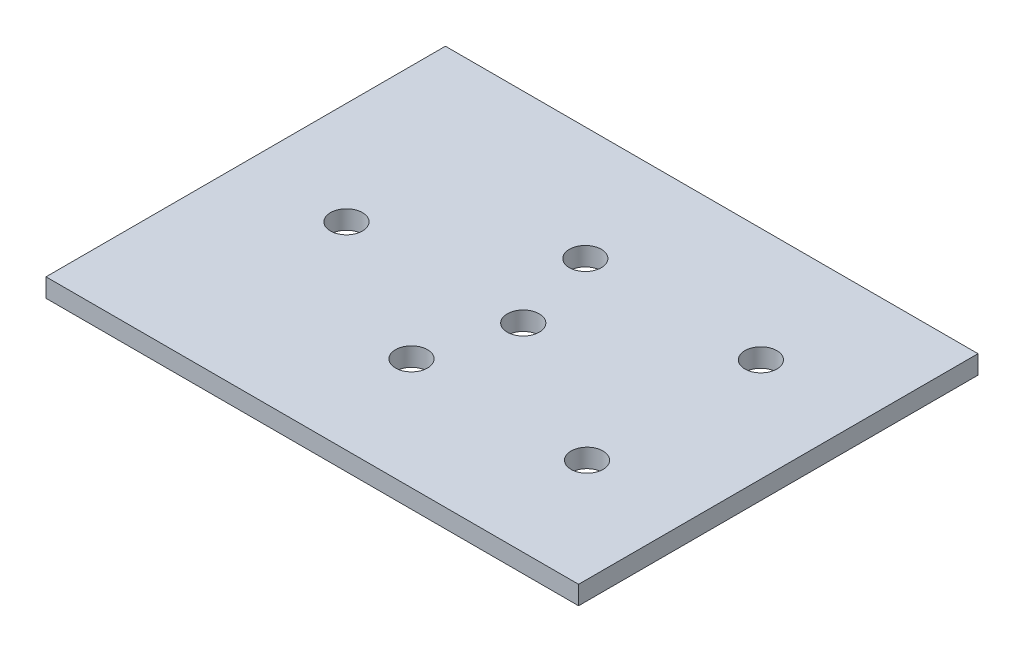
SolidWorks part; units mm, degrees
ref_plane "Front Plane" through (0, 0, 0) normal (0, 0, 1) x (1, 0, 0)
ref_plane "Top Plane" through (0, 0, 0) normal (0, 1, 0) x (1, 0, 0)
ref_plane "Right Plane" through (0, 0, 0) normal (1, 0, 0) x (0, 0, -1)
sketch "Sketch1" plane through (0, 0, 0) normal (0, 1, 0) x (1, 0, 0)
  line L0 (-63.449, 23.2484) -> (36.551, 23.2484)
  line L1 (36.551, 23.2484) -> (36.551, -51.7516)
  line L2 (-63.449, 23.2484) -> (-63.449, -51.7516)
  line L3 (-63.449, -51.7516) -> (36.551, -51.7516)
extrude "Boss-Extrude1" add sketch "Sketch1" along normal blind 3.5
hole_wizard "Ø6.0mm Dowel Hole1" positions "Sketch2" profile "Sketch3" hole size "Ø6.0" standard "ANSI Metric"
sketch "Sketch2" plane through (-137.5284, 0, 99.0346) normal (0, -1, 0) x (-1, 0, 0)
  point P0 (-156.2989, 100.9147)
sketch "Sketch3" plane through (18.7704, 0, -1.8801) normal (1, 0, 0) x (0, 0, -1)
  line L0 (0, 0) -> (0, 7.0026)
  line L1 (0, 7.0026) -> (3, 5.2)
  line L2 (3, 5.2) -> (3, 0)
  line L3 (3, 0) -> (0, 0)
  line L4 (0, 7.0026) -> (-3, 5.2) construction
  line L5 (0, -6.35) -> (0, 107.95) construction
  dimension "Hole Dia." = 6
  dimension "Hole Depth" = 5.2
  dimension "Drill Angle" = 118
hole_wizard "Ø6.0mm Dowel Hole2" positions "Sketch4" profile "Sketch5" hole size "Ø6.0" standard "ANSI Metric"
sketch "Sketch4" plane through (-137.5284, 0, 99.0346) normal (0, -1, 0) x (-1, 0, 0)
  point P0 (-123.3367, 100.9147)
sketch "Sketch5" plane through (-14.1917, 0, -1.8801) normal (1, 0, 0) x (0, 0, -1)
  line L0 (0, 0) -> (0, 7.0026)
  line L1 (0, 7.0026) -> (3, 5.2)
  line L2 (3, 5.2) -> (3, 0)
  line L3 (3, 0) -> (0, 0)
  line L4 (0, 7.0026) -> (-3, 5.2) construction
  line L5 (0, -6.35) -> (0, 107.95) construction
  dimension "Hole Dia." = 6
  dimension "Hole Depth" = 5.2
  dimension "Drill Angle" = 118
hole_wizard "Ø6.0mm Dowel Hole3" positions "Sketch6" profile "Sketch7" hole size "Ø6.0" standard "ANSI Metric"
sketch "Sketch6" plane through (-137.5284, 0, 99.0346) normal (0, -1, 0) x (-1, 0, 0)
  point P0 (-156.2989, 68.1913)
sketch "Sketch7" plane through (18.7704, 0, 30.8433) normal (1, 0, 0) x (0, 0, -1)
  line L0 (0, 0) -> (0, 7.0026)
  line L1 (0, 7.0026) -> (3, 5.2)
  line L2 (3, 5.2) -> (3, 0)
  line L3 (3, 0) -> (0, 0)
  line L4 (0, 7.0026) -> (-3, 5.2) construction
  line L5 (0, -6.35) -> (0, 107.95) construction
  dimension "Hole Dia." = 6
  dimension "Hole Depth" = 5.2
  dimension "Drill Angle" = 118
hole_wizard "Ø6.0mm Dowel Hole4" positions "Sketch8" profile "Sketch9" hole size "Ø6.0" standard "ANSI Metric"
sketch "Sketch8" plane through (-137.5284, 0, 99.0346) normal (0, -1, 0) x (-1, 0, 0)
  point P0 (-123.3367, 68.1913)
sketch "Sketch9" plane through (-14.1917, 0, 30.8433) normal (1, 0, 0) x (0, 0, -1)
  line L0 (0, 0) -> (0, 7.0026)
  line L1 (0, 7.0026) -> (3, 5.2)
  line L2 (3, 5.2) -> (3, 0)
  line L3 (3, 0) -> (0, 0)
  line L4 (0, 7.0026) -> (-3, 5.2) construction
  line L5 (0, -6.35) -> (0, 107.95) construction
  dimension "Hole Dia." = 6
  dimension "Hole Depth" = 5.2
  dimension "Drill Angle" = 118
hole_wizard "Ø6.0mm Dowel Hole5" positions "Sketch10" profile "Sketch11" hole size "Ø6.0" standard "ANSI Metric"
sketch "Sketch10" plane through (-137.5284, 0, 99.0346) normal (0, -1, 0) x (-1, 0, 0)
  point P0 (-154.6989, 100.9005)
sketch "Sketch11" plane through (17.1704, 0, -1.8659) normal (1, 0, 0) x (0, 0, -1)
  line L0 (0, 0) -> (0, 7.0026)
  line L1 (0, 7.0026) -> (3, 5.2)
  line L2 (3, 5.2) -> (3, 0)
  line L3 (3, 0) -> (0, 0)
  line L4 (0, 7.0026) -> (-3, 5.2) construction
  line L5 (0, -6.35) -> (0, 107.95) construction
  dimension "Hole Dia." = 6
  dimension "Hole Depth" = 5.2
  dimension "Drill Angle" = 118
hole_wizard "Ø6.0mm Dowel Hole6" positions "Sketch12" profile "Sketch13" hole size "Ø6.0" standard "ANSI Metric"
sketch "Sketch12" plane through (-137.5284, 0, 99.0346) normal (0, -1, 0) x (-1, 0, 0)
  point P0 (-121.7367, 100.9005)
sketch "Sketch13" plane through (-15.7917, 0, -1.8659) normal (1, 0, 0) x (0, 0, -1)
  line L0 (0, 0) -> (0, 7.0026)
  line L1 (0, 7.0026) -> (3, 5.2)
  line L2 (3, 5.2) -> (3, 0)
  line L3 (3, 0) -> (0, 0)
  line L4 (0, 7.0026) -> (-3, 5.2) construction
  line L5 (0, -6.35) -> (0, 107.95) construction
  dimension "Hole Dia." = 6
  dimension "Hole Depth" = 5.2
  dimension "Drill Angle" = 118
hole_wizard "Ø6.0mm Dowel Hole7" positions "Sketch14" profile "Sketch15" hole size "Ø6.0" standard "ANSI Metric"
sketch "Sketch14" plane through (-137.5284, 0, 99.0346) normal (0, -1, 0) x (-1, 0, 0)
  point P0 (-154.6989, 68.2553)
sketch "Sketch15" plane through (17.1704, 0, 30.7793) normal (1, 0, 0) x (0, 0, -1)
  line L0 (0, 0) -> (0, 7.0026)
  line L1 (0, 7.0026) -> (3, 5.2)
  line L2 (3, 5.2) -> (3, 0)
  line L3 (3, 0) -> (0, 0)
  line L4 (0, 7.0026) -> (-3, 5.2) construction
  line L5 (0, -6.35) -> (0, 107.95) construction
  dimension "Hole Dia." = 6
  dimension "Hole Depth" = 5.2
  dimension "Drill Angle" = 118
hole_wizard "Ø6.0mm Dowel Hole8" positions "Sketch16" profile "Sketch17" hole size "Ø6.0" standard "ANSI Metric"
sketch "Sketch16" plane through (-137.5284, 0, 99.0346) normal (0, -1, 0) x (-1, 0, 0)
  point P0 (-121.7367, 68.2553)
sketch "Sketch17" plane through (-15.7917, 0, 30.7793) normal (1, 0, 0) x (0, 0, -1)
  line L0 (0, 0) -> (0, 7.0026)
  line L1 (0, 7.0026) -> (3, 5.2)
  line L2 (3, 5.2) -> (3, 0)
  line L3 (3, 0) -> (0, 0)
  line L4 (0, 7.0026) -> (-3, 5.2) construction
  line L5 (0, -6.35) -> (0, 107.95) construction
  dimension "Hole Dia." = 6
  dimension "Hole Depth" = 5.2
  dimension "Drill Angle" = 118
hole_wizard "Ø6.0mm Dowel Hole9" positions "Sketch18" profile "Sketch19" hole size "Ø6.0" standard "ANSI Metric" end condition through all
sketch "Sketch18" plane through (-137.5284, 0, 99.0346) normal (0, -1, 0) x (-1, 0, 0)
  point P0 (-93.3466, 84.4369)
sketch "Sketch19" plane through (-44.1818, 0, 14.5977) normal (1, 0, 0) x (0, 0, -1)
  line L0 (0, 0) -> (0, 3.5)
  line L1 (0, 3.5) -> (3, 3.5)
  line L2 (3, 3.5) -> (3, 0)
  line L3 (3, 0) -> (0, 0)
  line L4 (0, -6.35) -> (0, 107.95) construction
  dimension "Thru Hole Dia." = 6
  dimension "Thru Hole Depth" = 3.5
hole_wizard "Ø6.0mm Dowel Hole10" positions "Sketch20" profile "Sketch21" hole size "Ø6.0" standard "AS" end condition through all
sketch "Sketch20" plane through (-137.5284, 0, 99.0346) normal (0, -1, 0) x (-1, 0, 0)
  point P0 (-126.3997, 84.5766)
sketch "Sketch21" plane through (-11.1287, 0, 14.458) normal (1, 0, 0) x (0, 0, -1)
  line L0 (0, 0) -> (0, 3.5)
  line L1 (0, 3.5) -> (3, 3.5)
  line L2 (3, 3.5) -> (3, 0)
  line L3 (3, 0) -> (0, 0)
  line L4 (0, -6.35) -> (0, 107.95) construction
  dimension "Thru Hole Dia." = 6
  dimension "Thru Hole Depth" = 3.5
